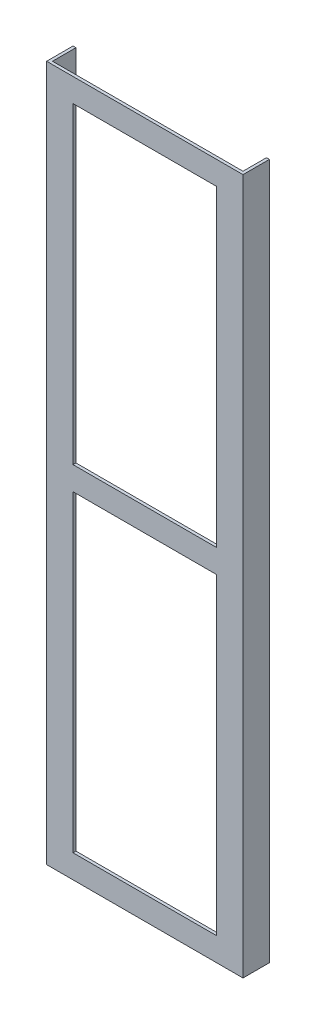
SolidWorks part; units mm, degrees
material "6061-T6 (SS)"
ref_plane "Front Plane" through (0, 0, 0) normal (0, 0, 1) x (1, 0, 0)
ref_plane "Top Plane" through (0, 0, 0) normal (0, 1, 0) x (1, 0, 0)
ref_plane "Right Plane" through (0, 0, 0) normal (1, 0, 0) x (0, 0, -1)
sketch "Sketch1" plane through (0, 0, 0) normal (0, 1, 0) x (1, 0, 0)
  line L0 (0, 50) -> (0, 41.5) construction
  line L1 (-50, 0) -> (-41.5, 0) construction
  line L2 (-50, 0) -> (-50, 50) construction
  line L3 (-50, 50) -> (50, 50) construction
  line L4 (50, 50) -> (50, -50) construction
  line L5 (50, -50) -> (-50, -50) construction
  line L6 (-50, -50) -> (-50, 0) construction
  line L7 (-41.5, 50) -> (-41.5, -50) construction
  line L8 (41.5, 50) -> (41.5, -50) construction
  line L9 (-50, 41.5) -> (50, 41.5) construction
  line L10 (-50, -41.5) -> (50, -41.5) construction
  line L11 (51.5875, 51.5875) -> (-51.5875, 51.5875)
  line L12 (50, 50) -> (-50, 50)
  line L13 (50, 50) -> (50, -50)
  line L14 (50, -50) -> (-50, -50)
  line L15 (-50, 50) -> (-50, -50)
  line L16 (-51.5875, 51.5875) -> (-51.5875, -51.5875)
  line L17 (51.5875, -51.5875) -> (-51.5875, -51.5875)
  line L18 (51.5875, 51.5875) -> (51.5875, -51.5875)
  line L47 (41.5, 0) -> (50, 0) construction
  line L52 (0, -41.5) -> (0, -50) construction
  circle A0 centre (0, 0) radius 76.2 construction
  dimension "D4" = 152.4
  dimension "D1" = 1.5875
extrude "BulkShellExtrude" add sketch "Sketch1" along normal blind 376.8
sketch "AirframeReferenceBottom" plane through (0, 0, 0) normal (0, 1, 0) x (1, 0, 0)
  circle A0 centre (0, 0) radius 76.2 construction
  dimension "D1" = 152.4
sketch "AxialReference" plane through (0, 0, 0) normal (1, 0, 0) x (0, 0, -1)
  line L0 (0, 0) -> (0, 376.8) construction
  line L1 (-51.5875, 376.8) -> (51.5875, 376.8) construction
sketch "AirframeReferenceTop" plane through (0, 376.8, 0) normal (0, 1, 0) x (1, 0, 0)
  circle A0 centre (0, 0) radius 76.2 construction
  dimension "D1" = 152.4
sketch "Sketch14" plane through (51.5875, 0, 0) normal (1, 0, 0) x (0, 0, -1)
  line L0 (-51.5875, 376.8) -> (-51.5875, 0) construction
  line L1 (-38.8875, 364.1) -> (38.8875, 364.1)
  line L2 (-38.8875, 364.1) -> (-38.8875, 12.7)
  line L3 (-38.8875, 12.7) -> (38.8875, 12.7)
  line L4 (38.8875, 364.1) -> (38.8875, 12.7)
  line L5 (51.5875, 376.8) -> (51.5875, 0) construction
  line L6 (76.2, 376.8) -> (-76.2, 376.8) construction
  line L7 (76.2, 0) -> (-76.2, 0) construction
  dimension "D1" = 12.7
  dimension "D2" = 12.7
  dimension "D3" = 12.7
  dimension "D4" = 12.7
extrude "SideWallCut" cut sketch "Sketch14" against normal blind 103.1875
pattern_circular "SideWallCutPattern" count 4 over 360 about axis through (0, 0, 0) along (0, 1, 0) of "SideWallCut"
sketch "Sketch20" plane through (0, 0, 51.5875) normal (0, 0, 1) x (1, 0, 0)
  line L0 (-38.8875, 188.4) -> (38.8875, 188.4) construction
  line L1 (-38.8875, 364.1) -> (38.8875, 364.1) construction
  line L2 (-38.8875, 364.1) -> (-38.8875, 12.7) construction
  line L3 (-38.8875, 12.7) -> (38.8875, 12.7) construction
  line L4 (38.8875, 364.1) -> (38.8875, 12.7) construction
  line L5 (-38.8875, 182.05) -> (38.8875, 182.05)
  line L6 (-38.8875, 194.75) -> (38.8875, 194.75)
  line L8 (-38.8875, 194.75) -> (38.8875, 194.75)
  line L9 (-38.8875, 194.75) -> (-38.8875, 182.05)
  line L10 (-38.8875, 182.05) -> (38.8875, 182.05)
  line L11 (38.8875, 194.75) -> (38.8875, 182.05)
  line M27 (-38.8875, 12.7) -> (-38.8875, 364.1)
  line M29 (38.8875, 364.1) -> (38.8875, 12.7)
  dimension "D1" = 6.35
  dimension "D2" = 6.35
extrude "CenterSupport" add sketch "Sketch20" against normal blind 1.5875 contours L6 L5 M27 M29
pattern_circular "CenterSupportPatternCirc" count 4 over 360 about axis through (0, 0, 0) along (0, 1, 0) of "CenterSupport"
sketch "Sketch22" plane through (51.5875, 0, 0) normal (1, 0, 0) x (0, 0, -1)
  line L0 (76.2, 0) -> (-76.2, 0) construction
  line L1 (-51.5875, 376.8) -> (-50, 376.8) construction
  line L2 (-51.5875, 376.8) -> (-51.5875, 0) construction
  line L3 (-51.5875, 0) -> (-50, 0) construction
  line L4 (-50, 376.8) -> (-50, 0) construction
  line L5 (76.2, 376.8) -> (-76.2, 376.8) construction
  line L6 (51.5875, 0) -> (50, 0) construction
  line L7 (51.5875, 0) -> (51.5875, 376.8) construction
  line L8 (51.5875, 376.8) -> (50, 376.8) construction
  line L9 (50, 0) -> (50, 376.8) construction
  line L11 (-50, 376.8) -> (50, 376.8)
  line L12 (-50, 376.8) -> (-50, 0)
  line L13 (-50, 0) -> (50, 0)
  line L14 (50, 376.8) -> (50, 0)
  dimension "D1" = 1.5875
  dimension "D2" = 1.5875
extrude "Cut-Extrude4" cut sketch "Sketch22" against normal blind 103.1875
sketch "Sketch23" plane through (51.5875, 0, 0) normal (1, 0, 0) x (0, 0, -1)
  line L1 (-51.5875, 376.8) -> (-50, 376.8)
  line L2 (-51.5875, 376.8) -> (-51.5875, 0)
  line L3 (-51.5875, 0) -> (-50, 0)
  line L4 (-50, 376.8) -> (-50, 0)
extrude "Boss-Extrude1" add sketch "Sketch23" along normal blind 1.5875
mirror "Mirror1" about plane through (0, 0, 0) normal (1, 0, 0) of "Boss-Extrude1"
sketch "Sketch24" plane through (0, 0, 50) normal (0, 0, -1) x (-1, 0, 0)
  line L0 (76.2, 0) -> (-76.2, 0) construction
  line L1 (-53.175, 376.8) -> (-51.5875, 376.8)
  line L2 (-53.175, 376.8) -> (-53.175, 0)
  line L3 (-53.175, 0) -> (-51.5875, 0)
  line L4 (-51.5875, 376.8) -> (-51.5875, 0)
  line L6 (53.175, 376.8) -> (51.5875, 376.8)
  line L7 (53.175, 376.8) -> (53.175, 0)
  line L8 (53.175, 0) -> (51.5875, 0)
  line L9 (51.5875, 376.8) -> (51.5875, 0)
  dimension "D1" = 1.5875
  dimension "D2" = 1.5875
extrude "Boss-Extrude2" add sketch "Sketch24" along normal blind 12.7
